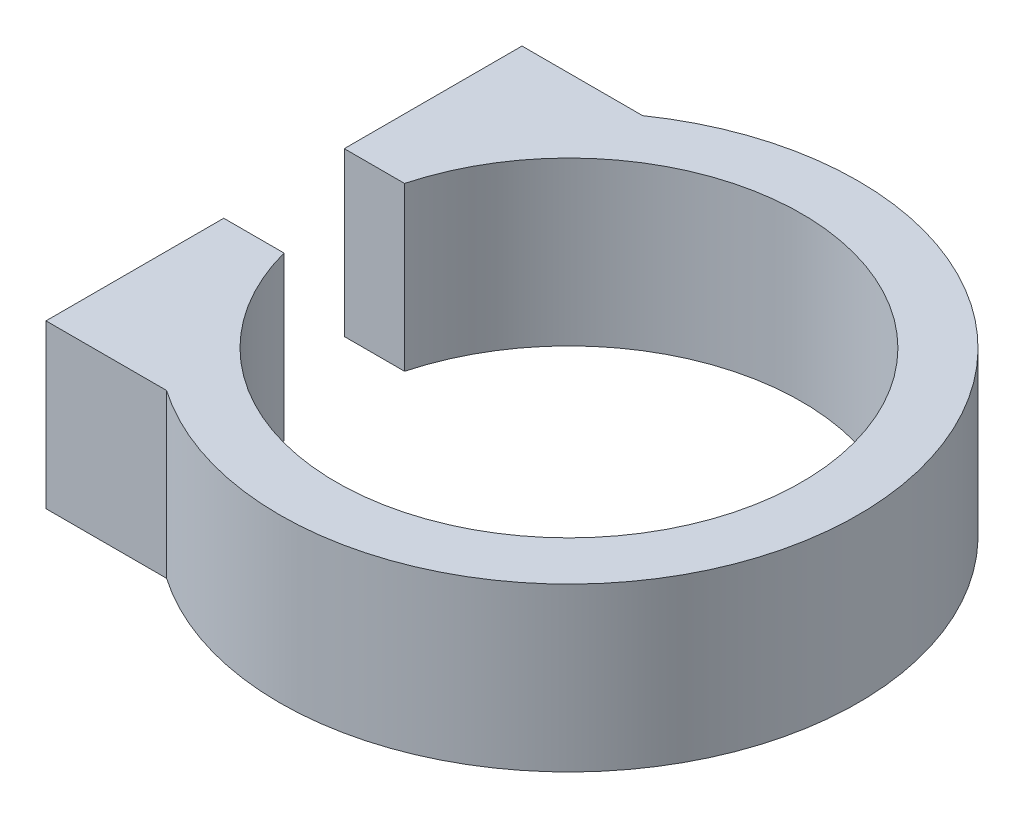
SolidWorks part; units mm, degrees
ref_plane "Front Plane" through (0, 0, 0) normal (0, 0, 1) x (1, 0, 0)
ref_plane "Top Plane" through (0, 0, 0) normal (0, 1, 0) x (1, 0, 0)
ref_plane "Right Plane" through (0, 0, 0) normal (1, 0, 0) x (0, 0, -1)
sketch "Sketch1" plane through (0, 0, 0) normal (0, 1, 0) x (1, 0, 0)
  line L1 (-23.6411, 5) -> (-23.6411, 19.7464)
  line L2 (-23.6411, 19.7464) -> (-13.6411, 19.7464)
  line L4 (-23.6411, -5) -> (-23.6411, -19.7464)
  line L7 (-23.6411, -19.7464) -> (-13.6411, -19.7464)
  line L8 (-18.6411, 5) -> (-23.6411, 5)
  line L9 (-18.6411, -5) -> (-23.6411, -5)
  arc A0 (-18.6411, 5) -> (-18.6411, -5) centre (0, 0) cw
  arc A1 (-13.6411, 19.7464) -> (-13.6411, -19.7464) centre (0, 0) cw
  point P8 (-21.67, -7.6088)
  point P9 (-18.7022, 4.7661)
  dimension "D1" = 19.3
  dimension "D2" = 24
  dimension "D3" = 5
  dimension "D4" = 10
  dimension "D5" = 10
extrude "Boss-Extrude1" add sketch "Sketch1" along normal blind 13.5
